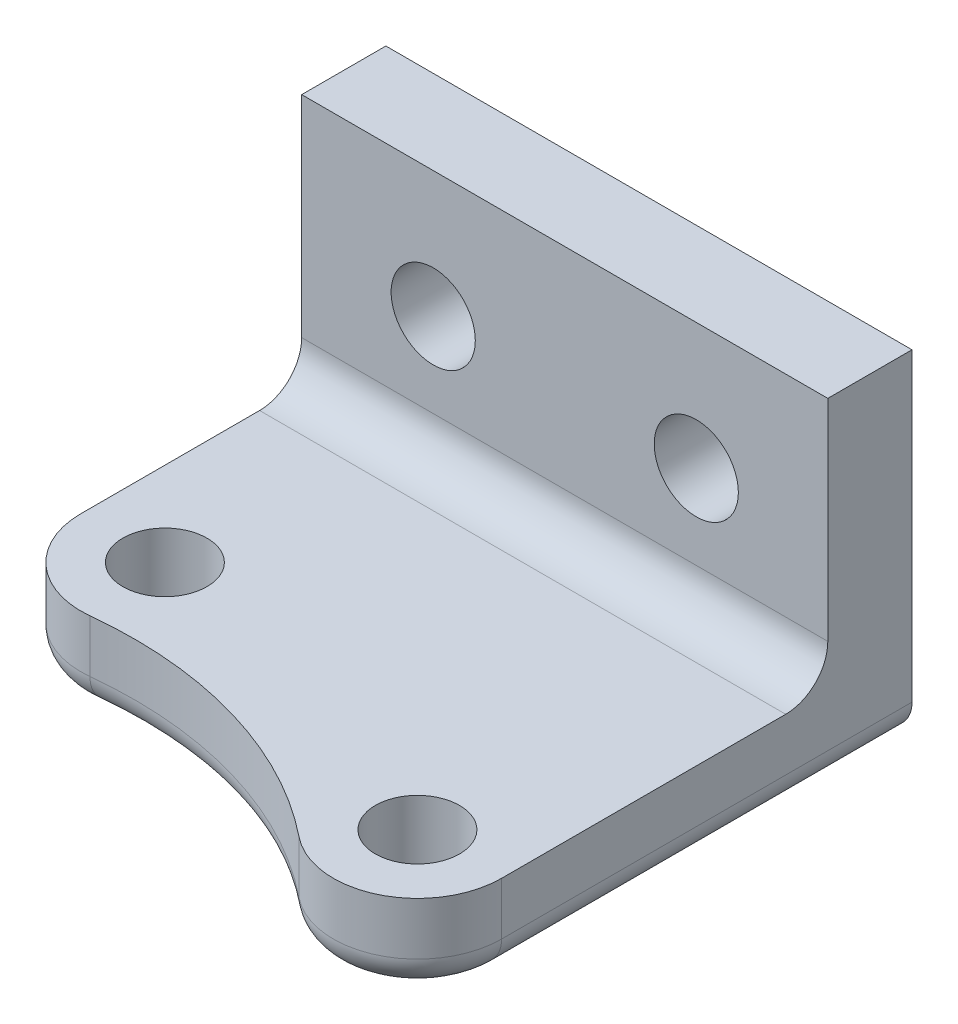
SolidWorks part; units mm, degrees
ref_plane "Front Plane" through (0, 0, 0) normal (0, 0, 1) x (1, 0, 0)
ref_plane "Top Plane" through (0, 0, 0) normal (0, 1, 0) x (1, 0, 0)
ref_plane "Right Plane" through (0, 0, 0) normal (1, 0, 0) x (0, 0, -1)
sketch "Sketch1" plane through (0, 0, 0) normal (0, 1, 0) x (1, 0, 0)
  line L2 (-4, 14.5) -> (21, 14.5)
  line L3 (-4, 0) -> (-4, 14.5)
  line L5 (21, -5) -> (21, 14.5)
  circle A0 centre (0, 0) radius 2
  circle A1 centre (17, -5) radius 2
  arc A2 (-4, 0) -> (0.4189, -3.978) centre (0, 0) ccw
  arc A3 (14.4941, -8.1177) -> (21, -5) centre (17, -5) ccw
  arc A4 (14.4941, -8.1177) -> (0.4189, -3.978) centre (2.435, -23.1211) ccw
extrude "Boss-Extrude1" add sketch "Sketch1" along normal blind 4
sketch "Sketch2" plane through (0, 4, 0) normal (0, 1, 0) x (1, 0, 0)
  line L0 (-4, 14.5) -> (-4, 10.5)
  line L1 (-4, 14.5) -> (-4, 0) construction
  line L2 (-4, 10.5) -> (21, 10.5)
  line L3 (21, -5) -> (21, 14.5) construction
  line L4 (21, 10.5) -> (21, 14.5)
  line L5 (21, 14.5) -> (-4, 14.5)
extrude "Boss-Extrude2" add sketch "Sketch2" along normal blind 12
sketch "Sketch3" plane through (0, 0, -10.5) normal (0, 0, 1) x (1, 0, 0)
  circle A0 centre (2.25, 10) radius 2
  circle A1 centre (14.75, 10) radius 2
extrude "Cut-Extrude1" cut sketch "Sketch3" against normal blind 12
fillet "Fillet1" radius 2 1 edges at (8.5, 4, -10.5)
fillet "Fillet2" radius 1.5 5 edges at (-4, 0, -7.25) (-2.6762, 0, 2.9729) (21, 0, -4.75) (18.7286, 0, 8.6072) (7.8664, 0, 4.6543)
